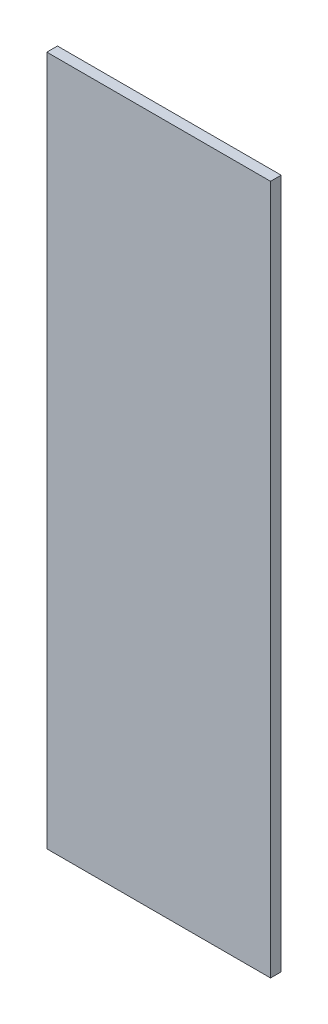
SolidWorks part; units mm, degrees
material "Polyurethane Foam Rigid"
ref_plane "Front Plane" through (0, 0, 0) normal (0, 0, 1) x (1, 0, 0)
ref_plane "Top Plane" through (0, 0, 0) normal (0, 1, 0) x (1, 0, 0)
ref_plane "Right Plane" through (0, 0, 0) normal (1, 0, 0) x (0, 0, -1)
sketch "Sketch1" plane through (0, 0, 0) normal (0, 0, 1) x (1, 0, 0)
  line L1 (-267.5, -825) -> (267.5, -825)
  line L2 (-267.5, -825) -> (-267.5, 825)
  line L3 (-267.5, 825) -> (267.5, 825)
  line L4 (267.5, -825) -> (267.5, 825)
  line L5 (-267.5, -825) -> (267.5, 825) construction
  line L6 (-267.5, 825) -> (267.5, -825) construction
  point P0 (0, 0)
  dimension "D1" = 535
  dimension "D2" = 1650
extrude "Boss-Extrude1" add sketch "Sketch1" along normal blind 25.4
